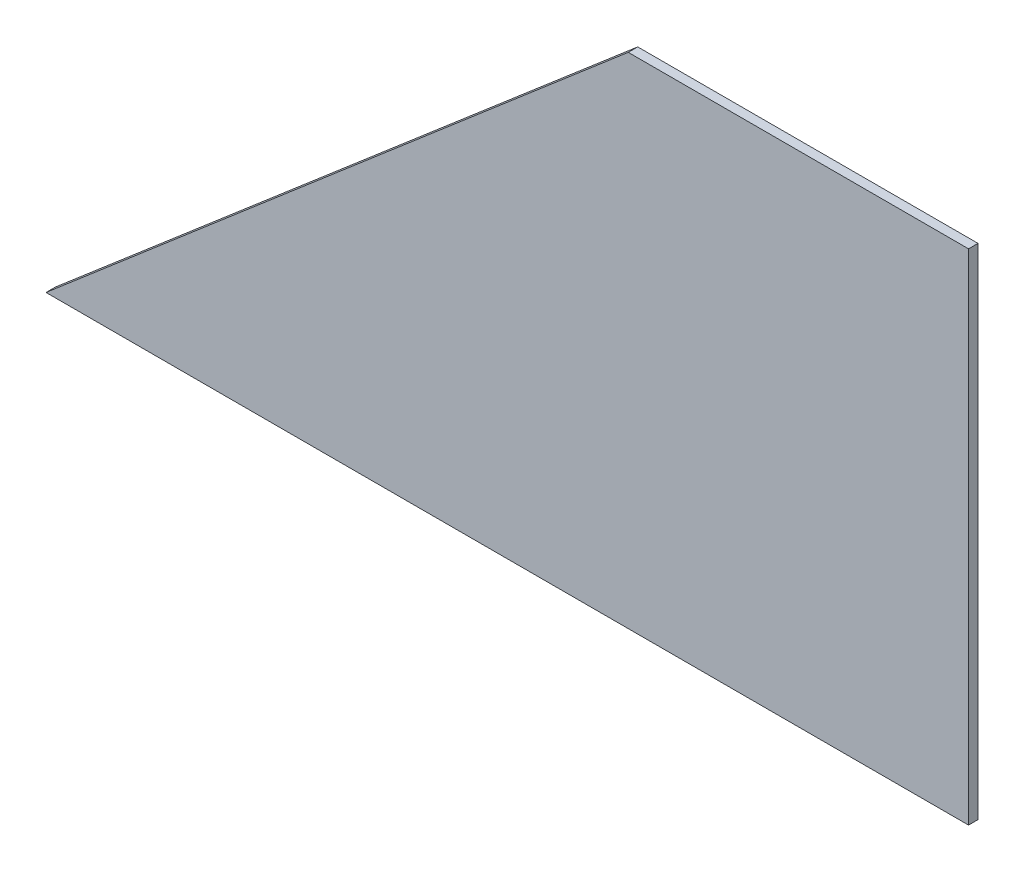
SolidWorks part; units mm, degrees
ref_plane "Front Plane" through (0, 0, 0) normal (0, 0, 1) x (1, 0, 0)
ref_plane "Top Plane" through (0, 0, 0) normal (0, 1, 0) x (1, 0, 0)
ref_plane "Right Plane" through (0, 0, 0) normal (1, 0, 0) x (0, 0, -1)
sketch "Sketch1" plane through (0, 0, 0) normal (0, 1, 0) x (1, 0, 0)
  line L1 (0, 0) -> (381, 0)
  line L2 (0, 0) -> (0, 50.8)
  line L3 (0, 50.8) -> (381, 50.8)
  line L4 (381, 0) -> (381, 50.8)
  dimension "D1" = 381
  dimension "D2" = 50.8
extrude "Boss-Extrude1" add sketch "Sketch1" along normal blind 10
ref_plane "Plane1" through (0, 0, -25.4) normal (0, 0, 1) x (1, 0, 0)
sketch "Sketch2" plane through (0, 0, -25.4) normal (0, 0, 1) x (1, 0, 0)
  line L0 (347.868, 10) -> (37.988, 10)
  line L1 (0, 10) -> (381, 10) construction
  line L2 (37.988, 10) -> (233.568, 177.64)
  line L3 (233.568, 177.64) -> (347.868, 177.64)
  line L4 (347.868, 177.64) -> (347.868, 10)
  dimension "D1" = 309.88
  dimension "D2" = 167.64
  dimension "D3" = 114.3
extrude "Boss-Extrude2" add sketch "Sketch2" along normal blind 1.5875 and the other way blind 1.5875 separate body
sketch "Sketch3" plane through (0, 10, 0) normal (0, 1, 0) x (1, 0, 0)
  line L4 (0, 50.8) -> (0, 0)
  line L5 (0, 0) -> (381, 0)
  line L6 (381, 0) -> (381, 50.8)
  line L7 (381, 50.8) -> (0, 50.8)
  line L8 (0, 50.8) -> (0, 0)
  line L9 (0, 0) -> (381, 0)
  line L10 (381, 0) -> (381, 50.8)
  line L11 (381, 50.8) -> (0, 50.8)
  dimension "D1" = 0
extrude "Cut-Extrude1" cut sketch "Sketch3" against normal through all
